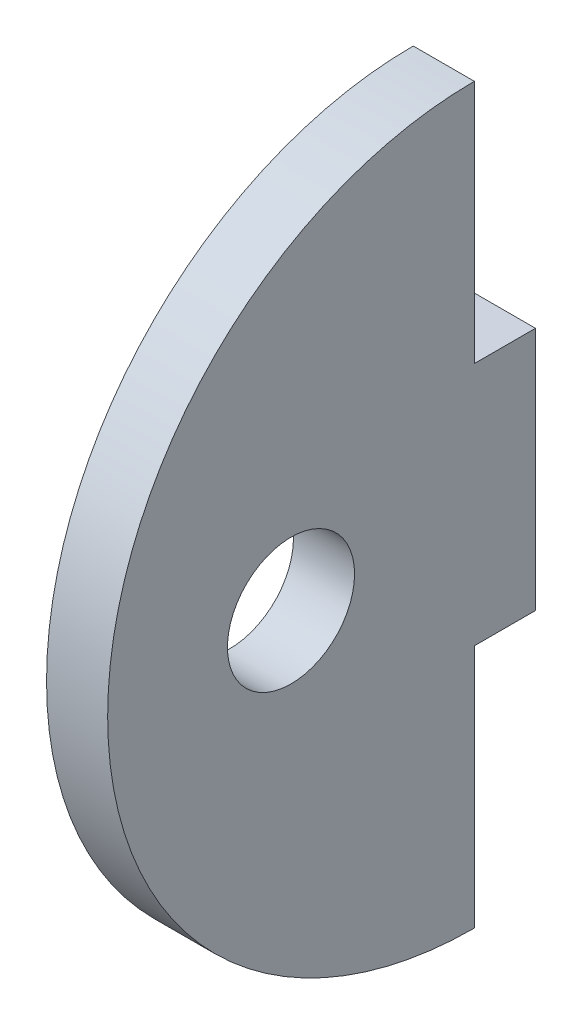
SolidWorks part; units mm, degrees
material "AISI 4340 Сталь, нормализованная"
ref_plane "Спереди" through (0, 0, 0) normal (0, 0, 1) x (1, 0, 0)
ref_plane "Сверху" through (0, 0, 0) normal (0, 1, 0) x (1, 0, 0)
ref_plane "Справа" through (0, 0, 0) normal (1, 0, 0) x (0, 0, -1)
sketch "Эскиз1" plane through (0, 0, 0) normal (1, 0, 0) x (0, 0, -1)
  line L0 (-5, 20) -> (-35, 20) construction
  line L1 (0, 0) -> (-5, 0)
  line L2 (0, 0) -> (0, 40)
  line L3 (0, 40) -> (-5, 40)
  line L4 (-5, -10) -> (-5, 0)
  line L5 (-5, 40) -> (-5, 50)
  arc A1 (-5, 50) -> (-5, -10) centre (-5, 20) ccw
  circle A2 centre (-20, 20) radius 5.2
  dimension "D1" = 40
  dimension "D2" = 5
extrude "Бобышка-Вытянуть1" add sketch "Эскиз1" along normal blind 5
sketch "Эскиз2" plane through (5, 0, 0) normal (1, 0, 0) x (0, 0, -1)
  line L0 (0, 0) -> (0, 40) construction
  line L1 (-5, 40) -> (0, 40)
  line L2 (-5, 40) -> (-5, 30)
  line L3 (-5, 30) -> (0, 30)
  line L4 (0, 40) -> (0, 30)
  line L6 (-5, 0) -> (0, 0)
  line L7 (-5, 0) -> (-5, 10)
  line L8 (-5, 10) -> (0, 10)
  line L9 (0, 0) -> (0, 10)
  dimension "D1" = 10
  dimension "D2" = 10
extrude "Вырез-Вытянуть1" cut sketch "Эскиз2" against normal through all
